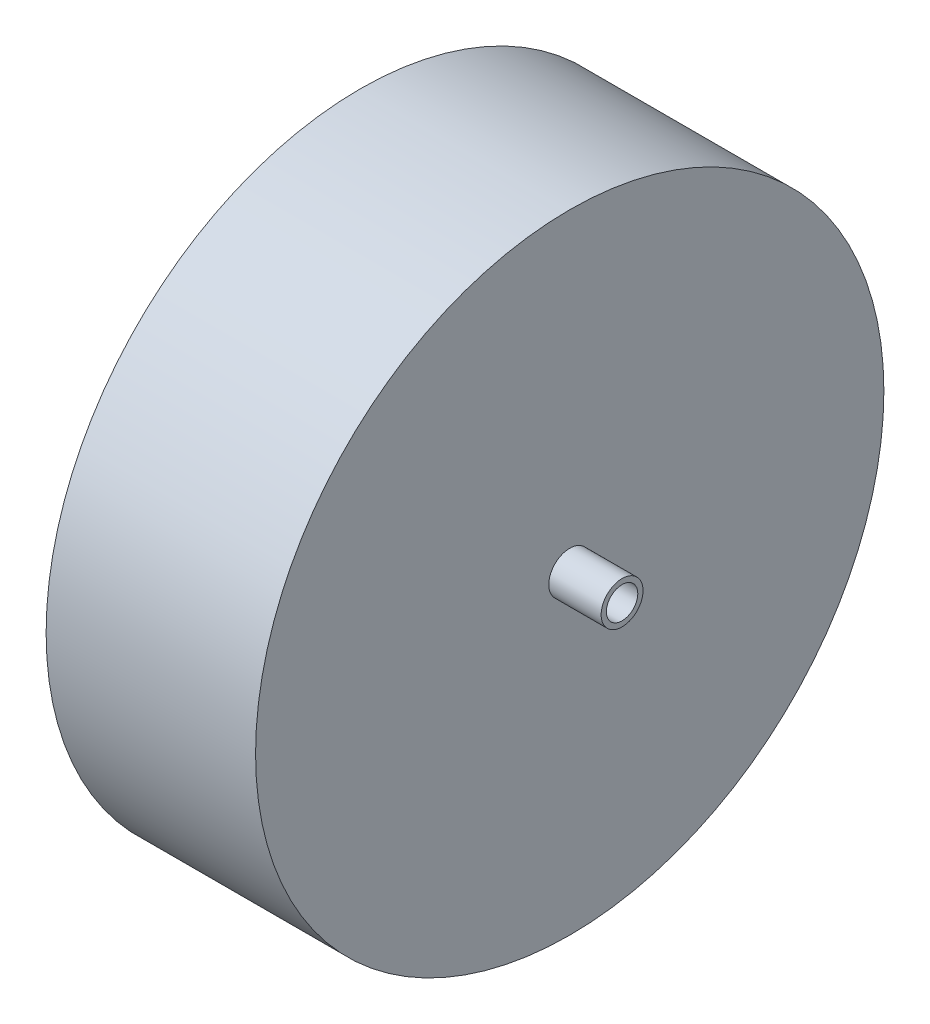
SolidWorks part; units mm, degrees
ref_plane "前视基准面" through (0, 0, 0) normal (0, 0, 1) x (1, 0, 0)
ref_plane "上视基准面" through (0, 0, 0) normal (0, 1, 0) x (1, 0, 0)
ref_plane "右视基准面" through (0, 0, 0) normal (1, 0, 0) x (0, 0, -1)
sketch "草图1" plane through (0, 0, 0) normal (1, 0, 0) x (0, 0, -1)
  circle A0 centre (0, 0) radius 3
  circle A1 centre (0, 0) radius 4
extrude "凸台-拉伸1" add sketch "草图1" along normal blind 10
sketch "草图2" plane through (0, 0, 0) normal (-1, 0, 0) x (0, 0, 1)
  circle A0 centre (0, 0) radius 60
extrude "凸台-拉伸2" add sketch "草图2" along normal blind 40
